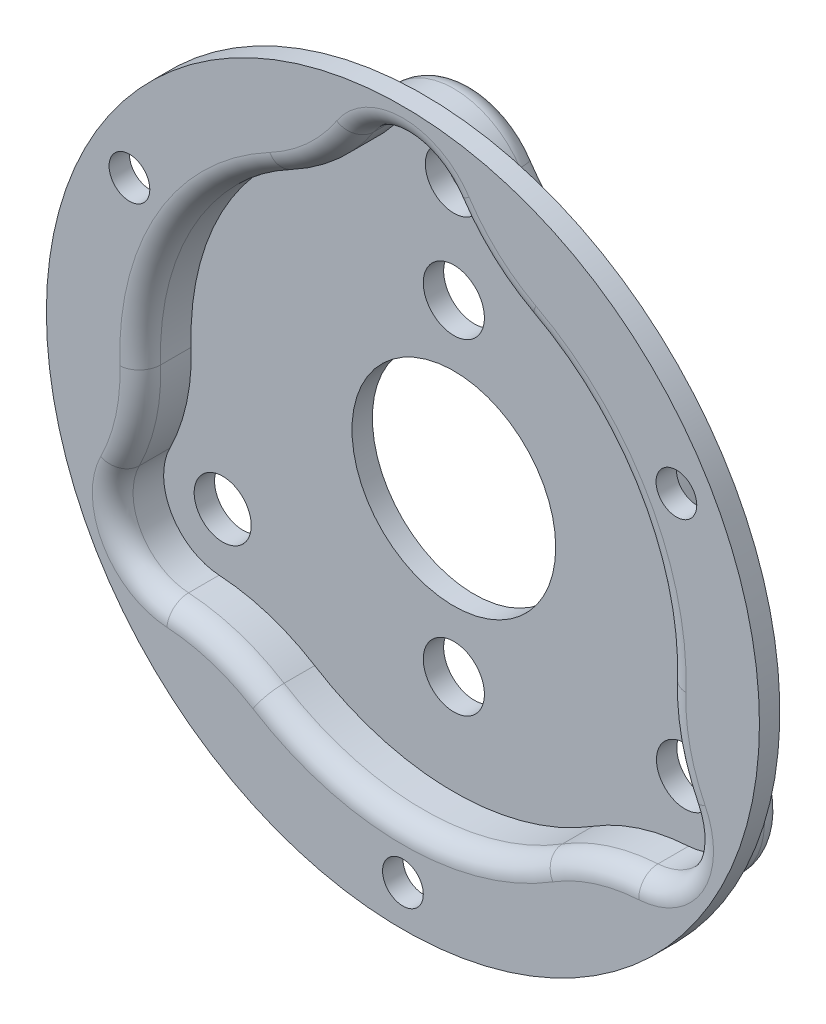
SolidWorks part; units mm, degrees
ref_plane "正面" through (0, 0, 0) normal (0, 0, 1) x (1, 0, 0)
ref_plane "平面" through (0, 0, 0) normal (0, 1, 0) x (1, 0, 0)
ref_plane "右側面" through (0, 0, 0) normal (1, 0, 0) x (0, 0, -1)
sketch "ｽｹｯﾁ1" plane through (0, 0, 0) normal (0, 0, 1) x (1, 0, 0)
  circle A0 centre (0, 0) radius 17.5
  dimension "D1" = 35
extrude "ﾎﾞｽ - 押し出し1" add sketch "ｽｹｯﾁ1" along normal blind 3.5
sketch "ｽｹｯﾁ2" plane through (0, 0, 3.5) normal (0, 0, 1) x (1, 0, 0)
  line L0 (0, 17.5) -> (0, 16) construction
  arc A0 (-2.8531, 12.5805) -> (-12.3216, -3.8194) centre (0, 0) ccw
  arc A1 (2.8531, 12.5805) -> (-2.8531, 12.5805) centre (0, 13.1) ccw
  arc A2 (9.4685, -8.7611) -> (12.3216, -3.8194) centre (11.3449, -6.55) ccw
  arc A3 (-12.3216, -3.8194) -> (-9.4685, -8.7611) centre (-11.3449, -6.55) ccw
  circle A4 centre (0, 0) radius 17.5 construction
  arc A5 (-9.4685, -8.7611) -> (9.4685, -8.7611) centre (0, 0) ccw
  arc A6 (12.3216, -3.8194) -> (2.8531, 12.5805) centre (0, 0) ccw
  point P11 (0, 0)
  dimension "D1" = 25.8
  dimension "D4" = 5.8
  dimension "D3" = 1.5
  dimension "D2" = 3
extrude "ｶｯﾄ - 押し出し1" cut sketch "ｽｹｯﾁ2" against normal blind 2.5
fillet "ﾌｨﾚｯﾄ1" radius 10 6 edges at (-12.3216, -3.8194, 2.25) (-9.4685, -8.7611, 2.25) (9.4685, -8.7611, 2.25) (12.3216, -3.8194, 2.25) (2.8531, 12.5805, 2.25) (-2.8531, 12.5805, 2.25)
sketch "ｽｹｯﾁ3" plane through (0, 0, 0) normal (0, 0, -1) x (-1, 0, 0)
  circle A13 centre (0, 0) radius 17.5
  circle A14 centre (0, 0) radius 17.5
  arc A24 (11.5809, -10.4429) -> (14.8342, -4.8079) centre (11.3449, -6.55) ccw
  arc A25 (11.5809, -10.4429) -> (7.36, -11.7915) centre (12.1254, -19.4264) ccw
  arc A26 (-7.36, -11.7915) -> (7.36, -11.7915) centre (0, 0) ccw
  arc A27 (-7.36, -11.7915) -> (-11.5809, -10.4429) centre (-12.1254, -19.4264) ccw
  arc A28 (-14.8342, -4.8079) -> (-11.5809, -10.4429) centre (-11.3449, -6.55) ccw
  arc A29 (-14.8342, -4.8079) -> (-13.8918, -0.4782) centre (-22.8864, -0.7878) ccw
  arc A30 (-6.5318, 12.2697) -> (-13.8918, -0.4782) centre (0, 0) ccw
  arc A31 (-6.5318, 12.2697) -> (-3.2533, 15.2508) centre (-10.761, 20.2141) ccw
  arc A32 (3.2533, 15.2508) -> (-3.2533, 15.2508) centre (0, 13.1) ccw
  arc A33 (3.2533, 15.2508) -> (6.5318, 12.2697) centre (10.761, 20.2141) ccw
  arc A34 (13.8918, -0.4782) -> (6.5318, 12.2697) centre (0, 0) ccw
  arc A35 (13.8918, -0.4782) -> (14.8342, -4.8079) centre (22.8864, -0.7878) ccw
  arc A36 (11.5809, -10.4429) -> (14.8342, -4.8079) centre (11.3449, -6.55) ccw
  arc A37 (11.5809, -10.4429) -> (7.36, -11.7915) centre (12.1254, -19.4264) ccw
  arc A38 (-7.36, -11.7915) -> (7.36, -11.7915) centre (0, 0) ccw
  arc A39 (-7.36, -11.7915) -> (-11.5809, -10.4429) centre (-12.1254, -19.4264) ccw
  arc A40 (-14.8342, -4.8079) -> (-11.5809, -10.4429) centre (-11.3449, -6.55) ccw
  arc A41 (-14.8342, -4.8079) -> (-13.8918, -0.4782) centre (-22.8864, -0.7878) ccw
  arc A42 (-6.5318, 12.2697) -> (-13.8918, -0.4782) centre (0, 0) ccw
  arc A43 (-6.5318, 12.2697) -> (-3.2533, 15.2508) centre (-10.761, 20.2141) ccw
  arc A44 (3.2533, 15.2508) -> (-3.2533, 15.2508) centre (0, 13.1) ccw
  arc A45 (3.2533, 15.2508) -> (6.5318, 12.2697) centre (10.761, 20.2141) ccw
  arc A46 (13.8918, -0.4782) -> (6.5318, 12.2697) centre (0, 0) ccw
  arc A47 (13.8918, -0.4782) -> (14.8342, -4.8079) centre (22.8864, -0.7878) ccw
  dimension "D1" = 1
  dimension "D2" = 0
extrude "ｶｯﾄ - 押し出し2" cut sketch "ｽｹｯﾁ3" against normal blind 2.5
fillet "ﾌｨﾚｯﾄ2" radius 1 12 edges at (4.0335, 12.8155, 3.5) (11.1717, 6.45, 3.5) (13.1152, -2.9146, 3.5) (13.8564, -8, 3.5) (9.0818, -9.9008, 3.5) (0, -12.9, 3.5) (-9.0818, -9.9008, 3.5) (-13.8564, -8, 3.5) (-13.1152, -2.9146, 3.5) (-11.1717, 6.45, 3.5) (-4.0335, 12.8155, 3.5) (0, 16, 3.5)
fillet "ﾌｨﾚｯﾄ3" radius 1 12 edges at (0, -13.9, 0) (9.3861, -10.8534, 0) (14.7224, -8.5, 0) (14.0924, -2.702, 0) (12.0378, 6.95, 0) (4.7062, 13.5553, 0) (0, 17, 0) (-4.7062, 13.5553, 0) (-12.0378, 6.95, 0) (-14.0924, -2.702, 0) (-14.7224, -8.5, 0) (-9.3861, -10.8534, 0)
sketch "ｽｹｯﾁ4" plane through (0, 0, 3.5) normal (0, 0, 1) x (1, 0, 0)
  line L0 (-17.5, 0) -> (17.5, 0) construction
  circle A0 centre (0, 13.1) radius 1.4
  circle A1 centre (0, -15.5) radius 1
  circle A2 centre (0, 0) radius 17.5 construction
  circle A3 centre (11.3449, -6.55) radius 1.4
  circle A4 centre (-13.4234, 7.75) radius 1
  circle A5 centre (-11.3449, -6.55) radius 1.4
  circle A6 centre (13.4234, 7.75) radius 1
  circle A7 centre (0, 8) radius 1.5
  circle A8 centre (0, 0) radius 5
  circle A9 centre (0, -8) radius 1.5
  point P19 (0, 0)
  point P21 (0, 0)
  point P29 (0, 0)
  dimension "D1" = 2.8
  dimension "D2" = 2
  dimension "D3" = 15.5
  dimension "D5" = 8
  dimension "D6" = 3
  dimension "D7" = 10
  dimension "D4" = 3
  dimension "D8" = 2
extrude "ｶｯﾄ - 押し出し3" cut sketch "ｽｹｯﾁ4" against normal through all
